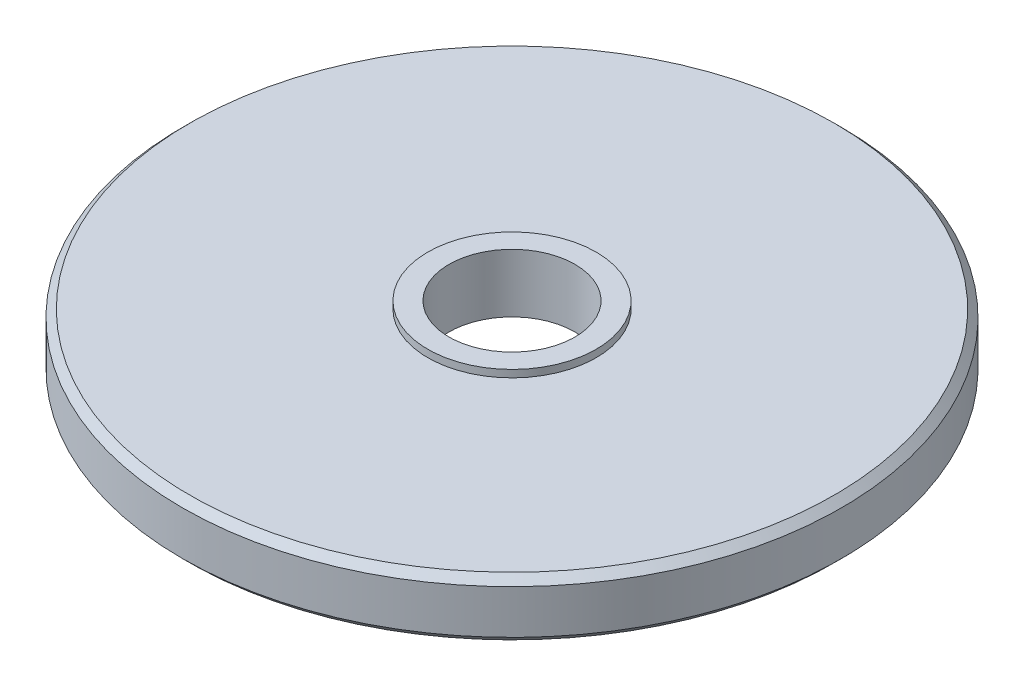
SolidWorks part; units mm, degrees
material "ПК/АБС"
ref_plane "Спереди" through (0, 0, 0) normal (0, 0, 1) x (1, 0, 0)
ref_plane "Сверху" through (0, 0, 0) normal (0, 1, 0) x (1, 0, 0)
ref_plane "Справа" through (0, 0, 0) normal (1, 0, 0) x (0, 0, -1)
sketch "Эскиз1" plane through (0, 0, 0) normal (0, 0, 1) x (1, 0, 0)
  line L0 (0, 0) -> (0, 87.1798) construction
  line L1 (-8.6, 29.7093) -> (-11.5, 29.7093)
  line L2 (-11.5, 29.7093) -> (-11.5, 28.7093)
  line L3 (-11.5, 28.7093) -> (-44, 28.7093)
  line L4 (-45, 27.7093) -> (-45, 21.7093)
  line L5 (-44, 20.7093) -> (-11, 20.7093)
  line L7 (-11, 21.7093) -> (-8.6, 21.7093)
  line L8 (-8.6, 29.7093) -> (-8.6, 21.7093)
  line L9 (-44, 28.7093) -> (-45, 27.7093)
  line L10 (-45, 21.7093) -> (-44, 20.7093)
  line L11 (-11, 21.7093) -> (-11, 20.7093)
  point P8 (-45, 20.7093)
  point P12 (-45, 28.7093)
  point P15 (-45, 28.7093)
  dimension "D8" = 7
  dimension "D1" = 8.6
  dimension "D2" = 11.5
  dimension "D3" = 11
  dimension "D4" = 1
  dimension "D5" = 8
  dimension "D6" = 45
revolve "Повернуть1" add sketch "Эскиз1" angle 360 about L0
